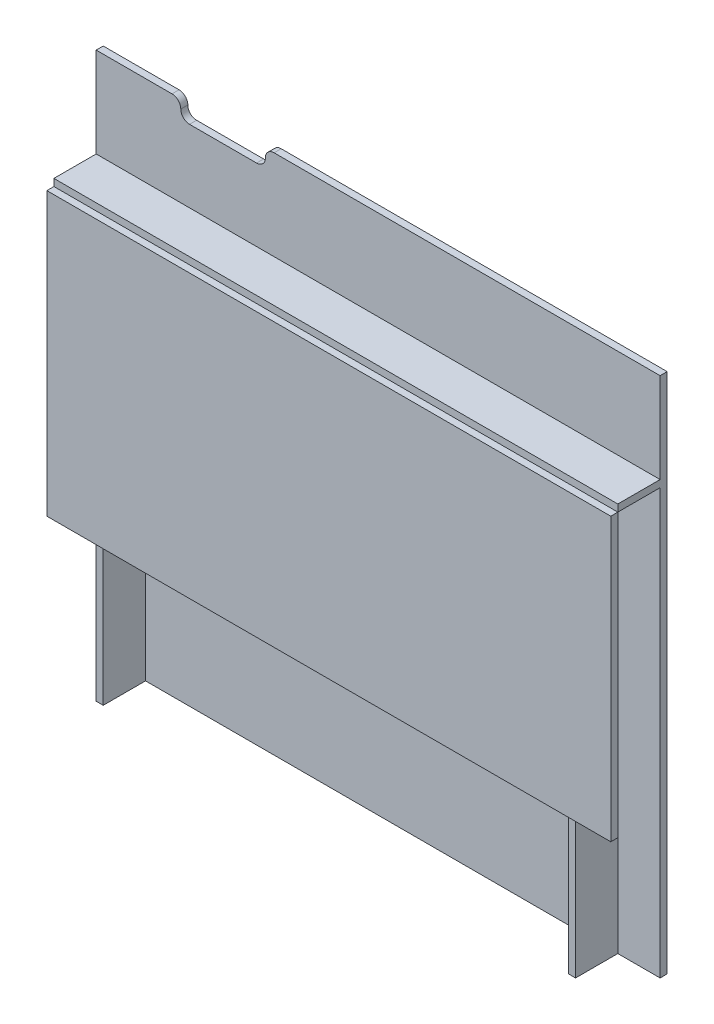
SolidWorks part; units mm, degrees
ref_plane "Front Plane" through (0, 0, 0) normal (0, 0, 1) x (1, 0, 0)
ref_plane "Top Plane" through (0, 0, 0) normal (0, 1, 0) x (1, 0, 0)
ref_plane "Right Plane" through (0, 0, 0) normal (1, 0, 0) x (0, 0, -1)
sketch "Sketch1" plane through (0, 0, 0) normal (0, 0, 1) x (1, 0, 0)
  line L1 (-508, -469.9) -> (508, -469.9)
  line L2 (-508, -469.9) -> (-508, 469.9)
  line L3 (-508, 469.9) -> (508, 469.9)
  line L4 (508, -469.9) -> (508, 469.9)
  line L5 (-508, -469.9) -> (508, 469.9) construction
  line L6 (-508, 469.9) -> (508, -469.9) construction
  point P0 (0, 0)
  dimension "D1" = 939.8
  dimension "D2" = 1016
extrude "Boss-Extrude1" add sketch "Sketch1" along normal blind 12.7
sketch "Sketch2" plane through (0, 0, 0) normal (0, 0, -1) x (-1, 0, 0)
  line L0 (-508, 438.15) -> (508, 438.15)
  line L1 (-508, -469.9) -> (-508, 469.9) construction
  line L2 (508, 469.9) -> (508, -469.9) construction
  line L3 (-508, 469.9) -> (508, 469.9) construction
  line L5 (203.2, 469.9) -> (355.6, 469.9)
  line L6 (203.2, 469.9) -> (203.2, 438.15)
  line L7 (203.2, 438.15) -> (355.6, 438.15)
  line L8 (355.6, 469.9) -> (355.6, 438.15)
  line M5 (508, 469.9) -> (-508, 469.9)
  dimension "D1" = 31.75
  dimension "D2" = 152.4
  dimension "D3" = 152.4
extrude "Cut-Extrude1" cut sketch "Sketch2" against normal through all contours L8 L6 L0 M5
fillet "Fillet1" radius 15.748 4 edges at (-203.2, 469.9, 6.35) (-355.6, 469.9, 6.35) (-355.6, 438.15, 6.35) (-203.2, 438.15, 6.35)
sketch "Sketch4" plane through (0, 0, 12.7) normal (0, 0, 1) x (1, 0, 0)
  line L0 (-508, 469.9) -> (-508, -469.9) construction
  line L1 (-508, 307.7992) -> (508, 307.7992)
  line L2 (-508, 307.7992) -> (-508, 295.0992)
  line L3 (-508, 295.0992) -> (508, 295.0992)
  line L4 (508, 307.7992) -> (508, 295.0992)
  line L5 (508, -469.9) -> (508, 469.9) construction
  dimension "D1" = 12.7
extrude "Boss-Extrude2" add sketch "Sketch4" along normal blind 76.2
sketch "Sketch5" plane through (0, 0, 12.7) normal (0, 0, 1) x (1, 0, 0)
  line L0 (-508, -469.9) -> (508, -469.9) construction
  line L1 (-431.8, -469.9) -> (-419.1, -469.9)
  line L2 (-431.8, -469.9) -> (-431.8, 295.0992)
  line L3 (-431.8, 295.0992) -> (-419.1, 295.0992)
  line L4 (-419.1, -469.9) -> (-419.1, 295.0992)
  line L5 (-508, 295.0992) -> (508, 295.0992) construction
  line L6 (-508, 295.0992) -> (-508, -469.9) construction
  line L7 (508, -469.9) -> (508, 295.0992) construction
  line L8 (431.8, -469.9) -> (419.1, -469.9)
  line L9 (431.8, -469.9) -> (431.8, 295.0992)
  line L10 (431.8, 295.0992) -> (419.1, 295.0992)
  line L11 (419.1, -469.9) -> (419.1, 295.0992)
  dimension "D1" = 12.7
  dimension "D2" = 76.2
  dimension "D3" = 76.2
  dimension "D4" = 12.7
extrude "Boss-Extrude3" add sketch "Sketch5" along normal blind 76.2
sketch "Sketch8" plane through (0, 0, 88.9) normal (0, 0, 1) x (1, 0, 0)
  line L5 (508, -469.9) -> (508, 295.0992) construction
  line L6 (-508, 295.0992) -> (508, 295.0992)
  line L7 (-508, 295.0992) -> (-508, -212.9008)
  line L8 (-508, -212.9008) -> (508, -212.9008)
  line L9 (508, 295.0992) -> (508, -212.9008)
  dimension "D1" = 508
extrude "Boss-Extrude5" add sketch "Sketch8" along normal blind 12.7 separate body
